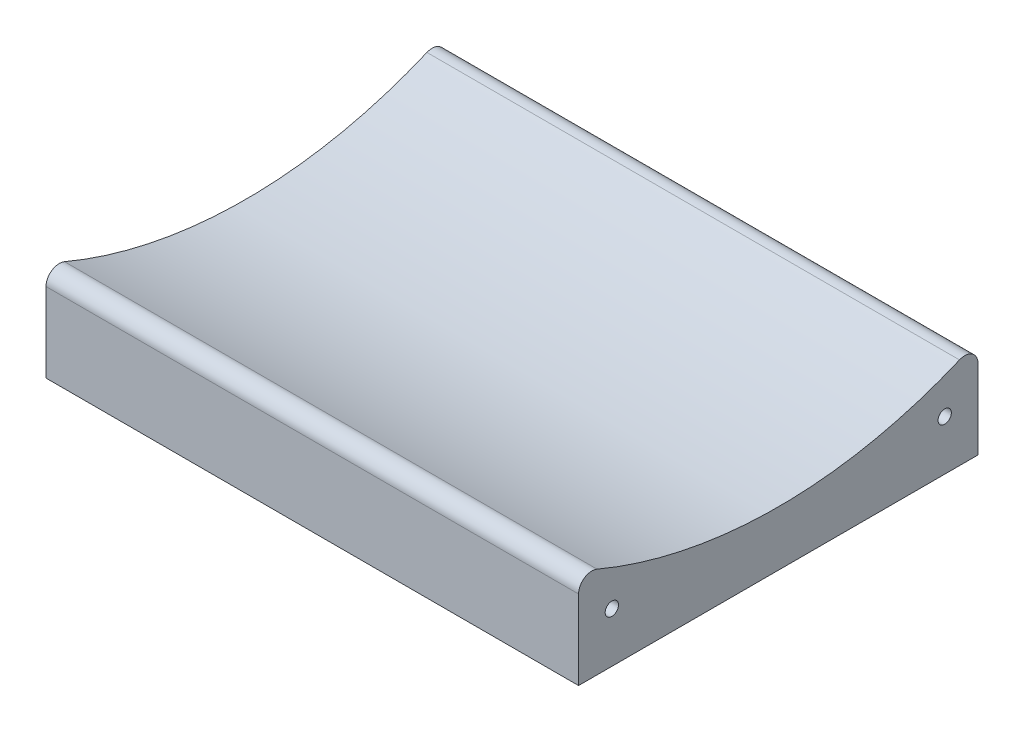
SolidWorks part; units mm, degrees
material "黄铜"
ref_plane "前视基准面" through (0, 0, 0) normal (0, 0, 1) x (1, 0, 0)
ref_plane "上视基准面" through (0, 0, 0) normal (0, 1, 0) x (1, 0, 0)
ref_plane "右视基准面" through (0, 0, 0) normal (1, 0, 0) x (0, 0, -1)
sketch "草图1" plane through (0, 0, 0) normal (1, 0, 0) x (0, 0, -1)
  line L0 (0, 0) -> (0, 41.1135) construction
  line L1 (-30, 0) -> (30, 0)
  line L2 (-30, 0) -> (-30, 15)
  line L3 (30, 0) -> (30, 15)
  arc A0 (-30, 15) -> (30, 15) centre (0, 78.2456) ccw
  dimension "D1" = 70
  dimension "D2" = 60
  dimension "D3" = 15
extrude "凸台-拉伸1" add sketch "草图1" along normal blind 80
fillet "圆角1" radius 2 2 edges at (40, 15, -30) (40, 15, 30)
sketch "草图2" plane through (80, 0, 0) normal (1, 0, 0) x (0, 0, -1)
  line L0 (0, 8.2456) -> (0, 0) construction
  line L1 (-30, 0) -> (30, 0) construction
  arc A0 (-27.2222, 13.7556) -> (27.2222, 13.7556) centre (0, 78.2456) ccw construction
  circle A1 centre (-25, 7.5) radius 1
  circle A2 centre (25, 7.5) radius 1
  dimension "D1" = 50
  dimension "D2" = 2
  dimension "D3" = 7.5
extrude "切除-拉伸1" cut sketch "草图2" against normal blind 5
ref_plane "基准面1" through (40, 0, 0) normal (1, 0, 0) x (0, 0, -1)
mirror "镜向1" about plane through (40, 0, 0) normal (1, 0, 0) of "切除-拉伸1"
sketch "草图3" plane through (0, 0, 0) normal (0, -1, 0) x (1, 0, 0)
  line L0 (0, 0) -> (80, 0) construction
  line L1 (80, 30) -> (80, -30) construction
  circle A0 centre (40, 0) radius 19.8655 construction
